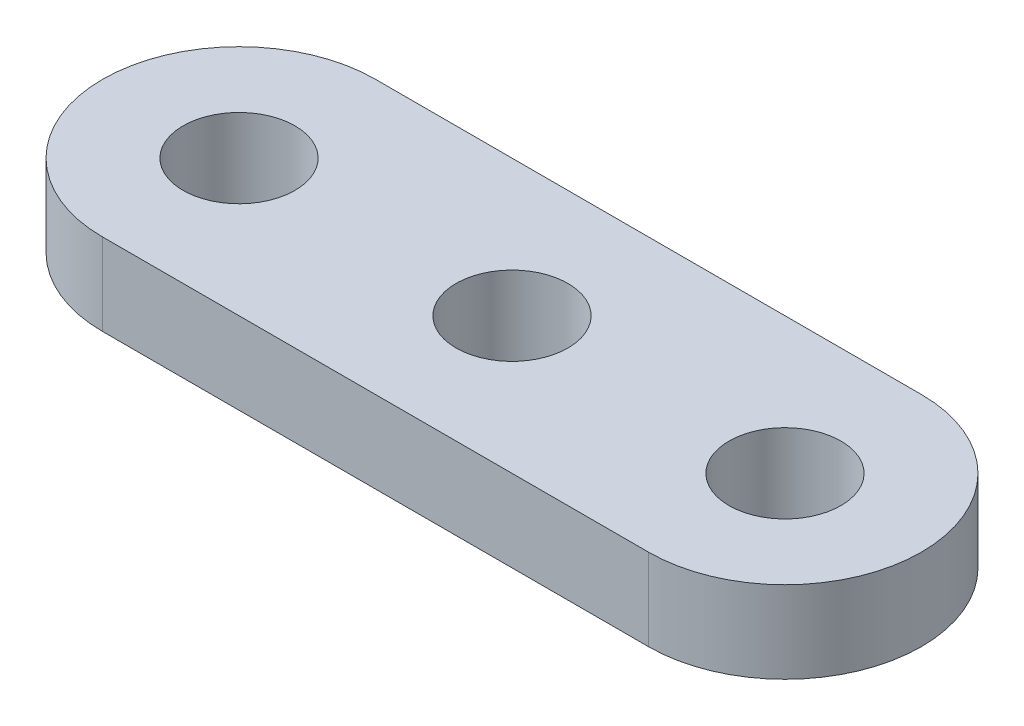
SolidWorks part; units mm, degrees
ref_plane "Front Plane" through (0, 0, 0) normal (0, 0, 1) x (1, 0, 0)
ref_plane "Top Plane" through (0, 0, 0) normal (0, 1, 0) x (1, 0, 0)
ref_plane "Right Plane" through (0, 0, 0) normal (1, 0, 0) x (0, 0, -1)
sketch "Sketch1" plane through (0, 0, 0) normal (0, 1, 0) x (1, 0, 0)
  line L0 (-10, -5) -> (-7.95, -5) construction
  line L1 (-10, 0) -> (-5, 0)
  line L2 (-10, -10) -> (-5, -10)
  line L3 (0, -33) -> (0, 33) construction
  line L4 (-5, 0) -> (5, 0)
  line L9 (5, 0) -> (10, 0)
  line L10 (0, 22.95) -> (0, 25) construction
  line L11 (-2.05, -5) -> (2.05, -5) construction
  line L12 (7.95, -5) -> (10, -5) construction
  line L14 (5, -10) -> (10, -10)
  line L15 (0, -7.05) -> (0, -2.95) construction
  line L16 (-5, -10) -> (5, -10)
  arc A0 (-10, 0) -> (-10, -10) centre (-10, -5) ccw
  arc A1 (10, -10) -> (10, 0) centre (10, -5) ccw
  circle A2 centre (10, -5) radius 2.05
  circle A3 centre (-10, -5) radius 2.05
  circle A4 centre (0, -5) radius 2.05
  point P2 (0, 0)
  point P18 (0, -5)
  dimension "D3" = 4.1
  dimension "D4" = 4.1
  dimension "D10" = 10
  dimension "D6" = 5
  dimension "D11" = 10
  dimension "D1" = 10
  dimension "D2" = 20
extrude "Boss-Extrude1" add sketch "Sketch1" along normal mid plane 3
